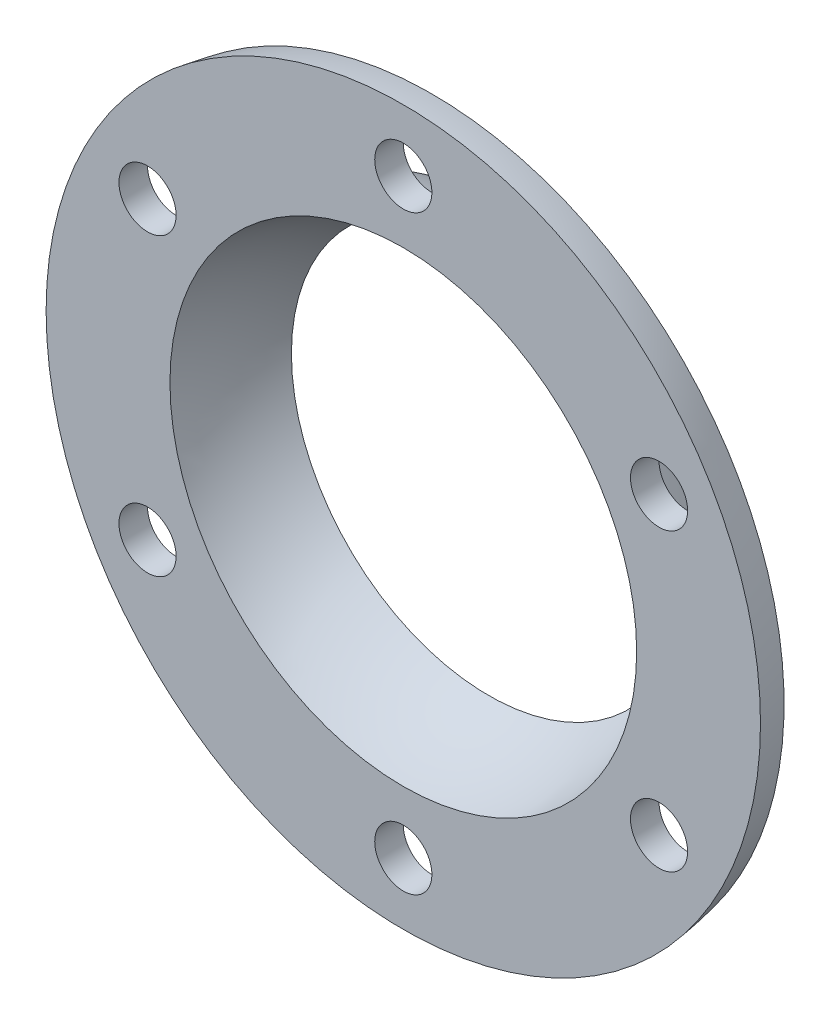
SolidWorks part; units mm, degrees
ref_plane "Front Plane" through (0, 0, 0) normal (0, 0, 1) x (1, 0, 0)
ref_plane "Top Plane" through (0, 0, 0) normal (0, 1, 0) x (1, 0, 0)
ref_plane "Right Plane" through (0, 0, 0) normal (1, 0, 0) x (0, 0, -1)
sketch "Sketch1" plane through (0, 0, 0) normal (0, 1, 0) x (1, 0, 0)
  line L0 (-42.821, 0) -> (37.4949, 0) construction
  line L1 (0, 42.3407) -> (0, -38.2321) construction
  line L7 (0, -5) -> (-42.821, -5) construction
  line L8 (24.4949, 0) -> (37.4949, 0)
  line L12 (26.8328, 3) -> (36.9719, 3)
  line L13 (37.4949, 0) -> (37.4949, 3) construction
  line L14 (20.7257, 8.9802) -> (24.2605, 8.9796)
  line L15 (37.4949, 3) -> (32.7183, 2.8693) construction
  line L16 (26.8328, 3) -> (29.7212, 3) construction
  line L17 (29.7212, 3) -> (29.7212, 3) construction
  line L18 (29.7212, 3) -> (29.7212, 3) construction
  arc A3 (25, -5) -> (-25, -5) centre (0, -5) ccw construction
  arc A4 (24, -5) -> (-24, -5) centre (0, -5) ccw construction
  arc A5 (20.7257, 8.9802) -> (24.4949, 0) centre (0, -5) cw
  arc A6 (24.2605, 8.9796) -> (26.8328, 3) centre (0, -5) cw
  arc A7 (23.2127, 10.6579) -> (26.8328, 3) centre (0, -5) cw construction
  arc A8 (37.8275, -5) -> (0, 32.8275) centre (0, -5) ccw construction
  arc A9 (-37.4956, 0) -> (-37.8275, -5) centre (0, -5) ccw construction
  arc A10 (37.4949, 0) -> (36.9719, 3) centre (0.2072, -4.9552) ccw
  dimension "D1" = 13
  dimension "D4" = 37.8275
  dimension "D2" = 3
  dimension "D3" = 25
  dimension "D5" = 5
revolve "Revolve1" add sketch "Sketch1" angle 360 about L1
sketch "Sketch8" plane through (0, 0, -3) normal (0, 0, -1) x (-1, 0, 0)
  line L0 (0, -40.8501) -> (0, -14.8455) construction
  line L1 (0, 36.9719) -> (0, 26.8328) construction
  circle A0 centre (0, 0) radius 36.9719 construction
  circle A1 centre (0, 0) radius 26.8328 construction
  circle A2 centre (0, 31) radius 3
  dimension "D1" = 31
extrude "Cut-Extrude3" cut sketch "Sketch8" against normal blind 10
pattern_circular "CirPattern2" count 6 over 360 about axis through (0, 0, 0) along (0, 0, 1) of "Cut-Extrude3"
